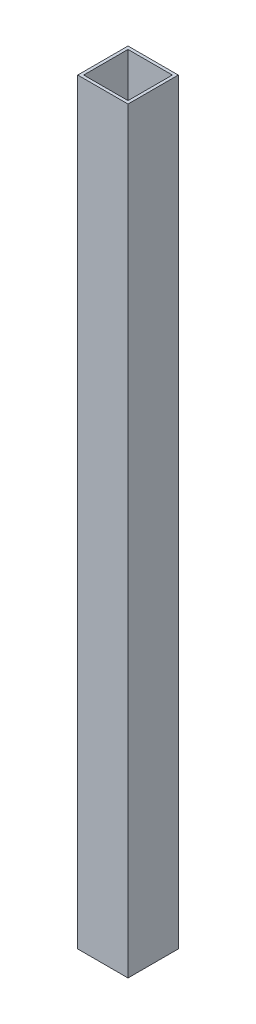
SolidWorks part; units mm, degrees
ref_plane "Front Plane" through (0, 0, 0) normal (0, 0, 1) x (1, 0, 0)
ref_plane "Top Plane" through (0, 0, 0) normal (0, 1, 0) x (1, 0, 0)
ref_plane "Right Plane" through (0, 0, 0) normal (1, 0, 0) x (0, 0, -1)
sketch "Sketch1" plane through (0, 0, 0) normal (0, 1, 0) x (1, 0, 0)
  line L1 (-8.5, 8.5) -> (8.5, 8.5)
  line L2 (-8.5, 8.5) -> (-8.5, -8.5)
  line L3 (-8.5, -8.5) -> (8.5, -8.5)
  line L4 (8.5, 8.5) -> (8.5, -8.5)
  line L5 (-8.5, 8.5) -> (8.5, -8.5) construction
  line L6 (-8.5, -8.5) -> (8.5, 8.5) construction
  line L7 (-7.5, 7.5) -> (7.5, 7.5)
  line L8 (-7.5, 7.5) -> (-7.5, -7.5)
  line L9 (-7.5, -7.5) -> (7.5, -7.5)
  line L10 (7.5, 7.5) -> (7.5, -7.5)
  line L11 (-7.5, 7.5) -> (7.5, -7.5) construction
  line L12 (-7.5, -7.5) -> (7.5, 7.5) construction
  point P0 (0, 0)
  point P6 (0, 0)
  dimension "D1" = 15
  dimension "D2" = 17
extrude "Boss-Extrude1" add sketch "Sketch1" along normal blind 256 contours L10 L9 L8 L7 | L4 L3 L2 L1
